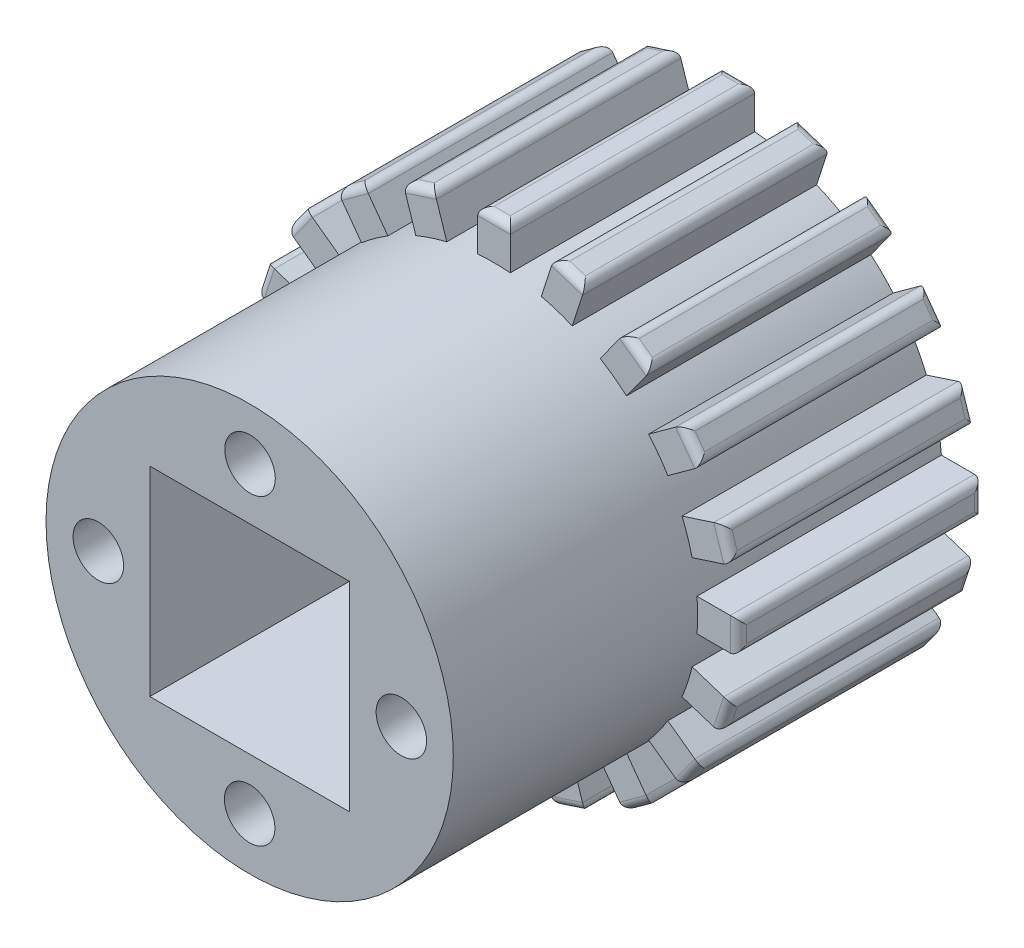
SolidWorks part; units mm, degrees
ref_plane "Front Plane" through (0, 0, 0) normal (0, 0, 1) x (1, 0, 0)
ref_plane "Top Plane" through (0, 0, 0) normal (0, 1, 0) x (1, 0, 0)
ref_plane "Right Plane" through (0, 0, 0) normal (1, 0, 0) x (0, 0, -1)
sketch "Sketch1" plane through (0, 0, 0) normal (0, 0, 1) x (1, 0, 0)
  circle A0 centre (0, 0) radius 12.5
  dimension "D2" = 25
extrude "Boss-Extrude1" add sketch "Sketch1" along normal mid plane 15
sketch "Sketch4" plane through (0, 0, 7.5) normal (0, 0, 1) x (1, 0, 0)
  line L0 (16.5, 0) -> (-16.5, 0) construction
  line L2 (-1, 0) -> (1, 0)
  line L3 (0, 0) -> (0, 15.8331) construction
  line L4 (-1, 0) -> (-1, 15)
  line L5 (-1, 15) -> (1, 15)
  line L6 (1, 0) -> (1, 15)
  circle A3 centre (0, 0) radius 12.5 construction
  point P9 (0, 0)
  dimension "D2" = 2
  dimension "D1" = 15
extrude "Boss-Extrude3" add sketch "Sketch4" against normal up to surface (15 mm away) up to face at (12.5, 0, -7.5)
fillet "Fillet1" radius 0.5 4 edges at (0, 15, -7.5) (0, 15, 7.5) (-1, 15, 0) (1, 15, 0)
pattern_circular "CirPattern7" count 20 over 360 about axis through (0, 0, 0) along (0, 0, 1) of "Boss-Extrude3", "Fillet1"
sketch "Sketch10" plane through (0, 0, 7.5) normal (0, 0, 1) x (1, 0, 0)
  circle A0 centre (0, 0) radius 12.5
  dimension "D1" = 25
extrude "Boss-Extrude4" add sketch "Sketch10" along normal blind 15
sketch "Sketch8" plane through (0, 0, 7.5) normal (0, 0, 1) x (1, 0, 0)
  line L2 (-6.125, 6.125) -> (6.125, 6.125)
  line L3 (-6.125, 6.125) -> (-6.125, -6.125)
  line L4 (-6.125, -6.125) -> (6.125, -6.125)
  line L5 (6.125, 6.125) -> (6.125, -6.125)
  line L6 (-6.125, 6.125) -> (6.125, -6.125) construction
  line L7 (-6.125, -6.125) -> (6.125, 6.125) construction
  point P5 (0, 0)
  point P14 (0, 0)
  dimension "D1" = 12.25
extrude "Cut-Extrude3" cut sketch "Sketch8" against normal up to next (15 mm away) from surface at 15 starting at face at (12.5, 0, 22.5)
sketch "Sketch9" plane through (0, 0, 7.5) normal (0, 0, 1) x (1, 0, 0)
  line L0 (13.75, 0) -> (-13.75, 0) construction
  line L1 (6.125, -6.125) -> (6.125, 6.125) construction
  circle A0 centre (9.3125, 0) radius 1.55
  circle A1 centre (0, -9.2875) radius 1.55
  circle A2 centre (-9.2875, 0.025) radius 1.55
  circle A3 centre (0.025, 9.3125) radius 1.55
  point P14 (0.0125, 0.0125)
  dimension "D1" = 3.1
  dimension "D2" = 3.1875
  dimension "D3" = 4
extrude "Cut-Extrude4" cut sketch "Sketch9" against normal through all from surface at 15 starting at face at (12.5, 0, 22.5)
equation "\"drumDiameter\"= 25"
equation "\"D2@Sketch1\"=\"drumDiameter\""
equation "\"drumLength\"= 15"
equation "\"foamThickness\"= 5"
equation "\"drumAbove\"= 0.6"
equation "\"holderThicc\"= 2"
equation "\"D2@Sketch4\"=\"holderThicc\""
equation "\"D1@Boss-Extrude1\"=\"drumLength\""
equation "\"squareBarLength\"= 12.25"
equation "\"D1@Sketch8\"=\"squareBarLength\""
equation "\"D2@Sketch9\"=(\"drumDiameter\"/2-\"squareBarLength\"/2)/2"
equation "\"D1@Sketch10\"=\"drumDiameter\""
equation "\"D1@Boss-Extrude4\"=\"drumLength\""
equation "\"toothlen\"= 2.5"
equation "\"D1@Sketch4\"=\"drumDiameter\"/2 + \"toothlen\""
